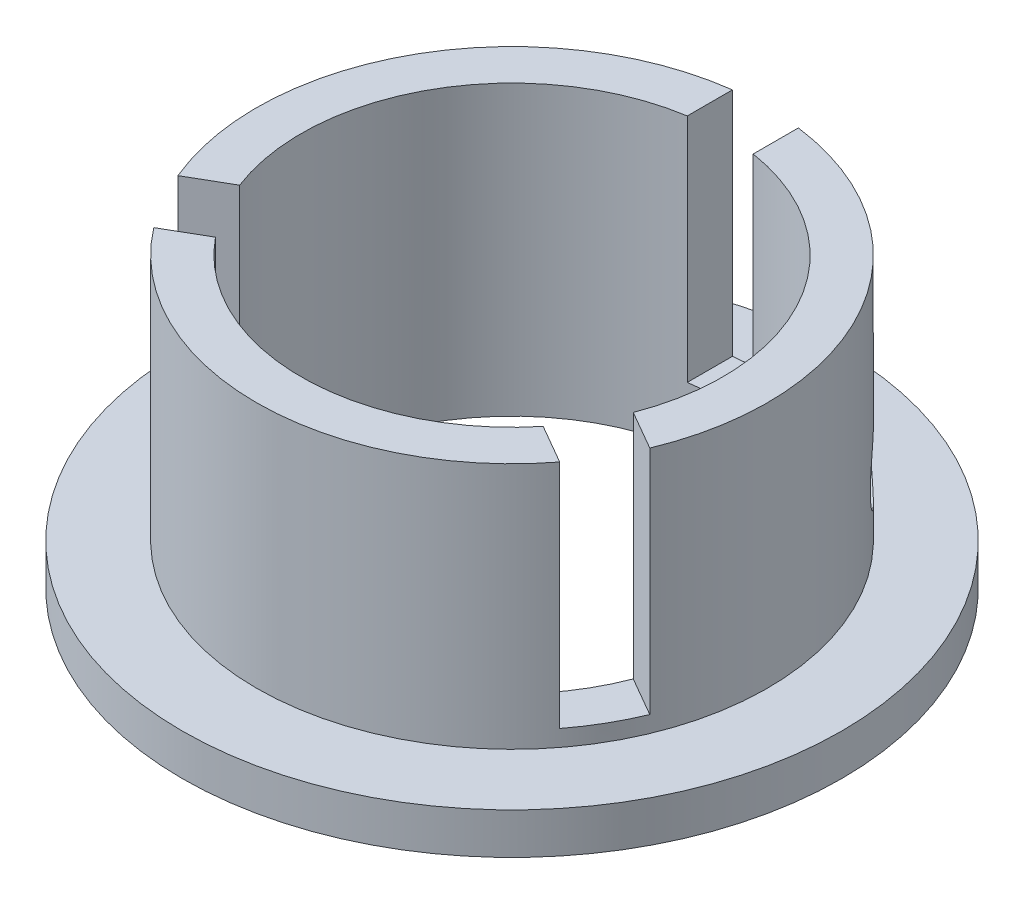
SolidWorks part; units mm, degrees
material "PET"
ref_plane "Alzado" through (0, 0, 0) normal (0, 0, 1) x (1, 0, 0)
ref_plane "Planta" through (0, 0, 0) normal (0, 1, 0) x (1, 0, 0)
ref_plane "Vista lateral" through (0, 0, 0) normal (1, 0, 0) x (0, 0, -1)
sketch "Croquis1" plane through (0, 0, 0) normal (0, 1, 0) x (1, 0, 0)
  circle A0 centre (0, 0) radius 12.7892
  circle A1 centre (0, 0) radius 20
  dimension "D1" = 40
extrude "Saliente-Extruir1" add sketch "Croquis1" along normal blind 2.5
sketch "Croquis2" plane through (0, 2.5, 0) normal (0, 1, 0) x (1, 0, 0)
  circle A0 centre (0, 0) radius 15.5
  circle A1 centre (0, 0) radius 12.7892 construction
  circle A2 centre (0, 0) radius 12.7892
  dimension "D1" = 31
extrude "Saliente-Extruir2" add sketch "Croquis2" along normal blind 15
sketch "Croquis3" plane through (0, 17.5, 0) normal (0, 1, 0) x (1, 0, 0)
  line L0 (0, 15.5) -> (0, 12.7892) construction
  line L1 (2, 15.3704) -> (2, 12.6318)
  line L2 (-2, 15.3704) -> (-2, 12.6318)
  circle A0 centre (0, 0) radius 15.5 construction
  circle A1 centre (0, 0) radius 12.7892 construction
  circle A2 centre (0, 0) radius 15.5 construction
  arc A3 (2, 15.3704) -> (-2, 15.3704) centre (0, 0) ccw
  arc A4 (2, 12.6318) -> (-2, 12.6318) centre (0, 0) ccw
  dimension "D1" = 4
extrude "Cortar-Extruir1" cut sketch "Croquis3" against normal blind 14
pattern_circular "MatrizC1" count 3 over 360 about axis through (0, 0, 0) along (0, 1, 0) of "Cortar-Extruir1"
ref_plane "Plano1" through (0, 0, 0) normal (-0.7071, 0, 0.7071) x (0.7071, 0, 0.7071)
sketch "Croquis4" plane through (0, 0, 0) normal (-0.7071, 0, 0.7071) x (0.7071, 0, 0.7071)
  line L0 (0, 2.5) -> (0, 17.5) construction
  line L1 (20, 2.5) -> (-20, 2.5) construction
  line L2 (14.3291, 17.5) -> (-9.4543, 17.5) construction
  circle A0 centre (0, 6.5) radius 2
  dimension "D1" = 4
  dimension "D2" = 4
extrude "Cortar-Extruir2" cut sketch "Croquis4" against normal blind 17
